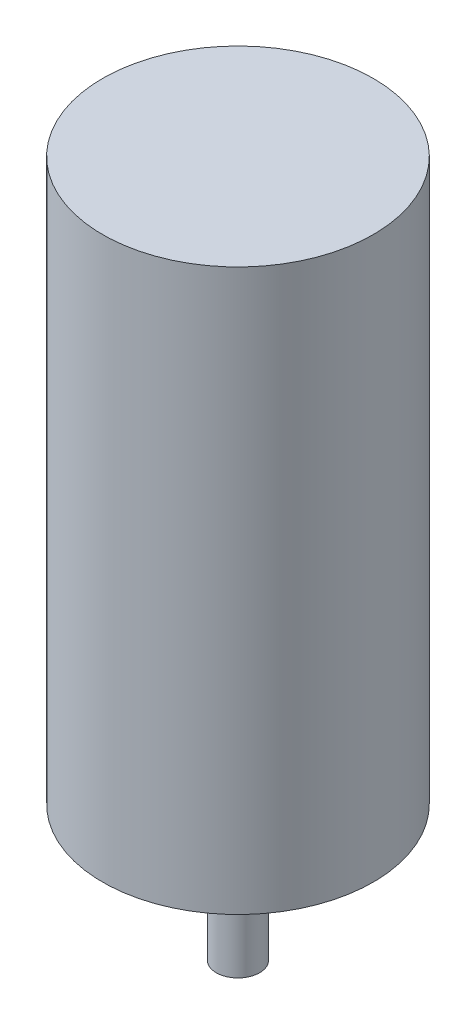
SolidWorks part; units mm, degrees
ref_plane "Front Plane" through (0, 0, 0) normal (0, 0, 1) x (1, 0, 0)
ref_plane "Top Plane" through (0, 0, 0) normal (0, 1, 0) x (1, 0, 0)
ref_plane "Right Plane" through (0, 0, 0) normal (1, 0, 0) x (0, 0, -1)
sketch "Sketch1" plane through (0, 0, 0) normal (0, 1, 0) x (1, 0, 0)
  circle A0 centre (0, 0) radius 12.5
  dimension "D1" = 25
extrude "Boss-Extrude1" add sketch "Sketch1" along normal blind 51.8
sketch "Sketch2" plane through (0, 0, 0) normal (0, -1, 0) x (-1, 0, 0)
  circle A0 centre (0, 0) radius 3.5
  dimension "D1" = 7
extrude "Boss-Extrude2" add sketch "Sketch2" along normal blind 2.5
sketch "Sketch3" plane through (0, -2.5, 0) normal (0, -1, 0) x (-1, 0, 0)
  circle A0 centre (0, 0) radius 2
  dimension "D1" = 4
extrude "Boss-Extrude3" add sketch "Sketch3" along normal blind 10
sketch "Sketch4" plane through (0, 0, 0) normal (0, -1, 0) x (-1, 0, 0)
  circle A0 centre (8.5, 0) radius 1.65
  circle A1 centre (-8.5, 0) radius 1.65
  dimension "D1" = 3.3
  dimension "D2" = 3.3
  dimension "D6" = 8.5
  dimension "D3" = 8.5
  dimension "D4" = 8.5
  dimension "D5" = 17
extrude "Cut-Extrude1" cut sketch "Sketch4" against normal blind 5
